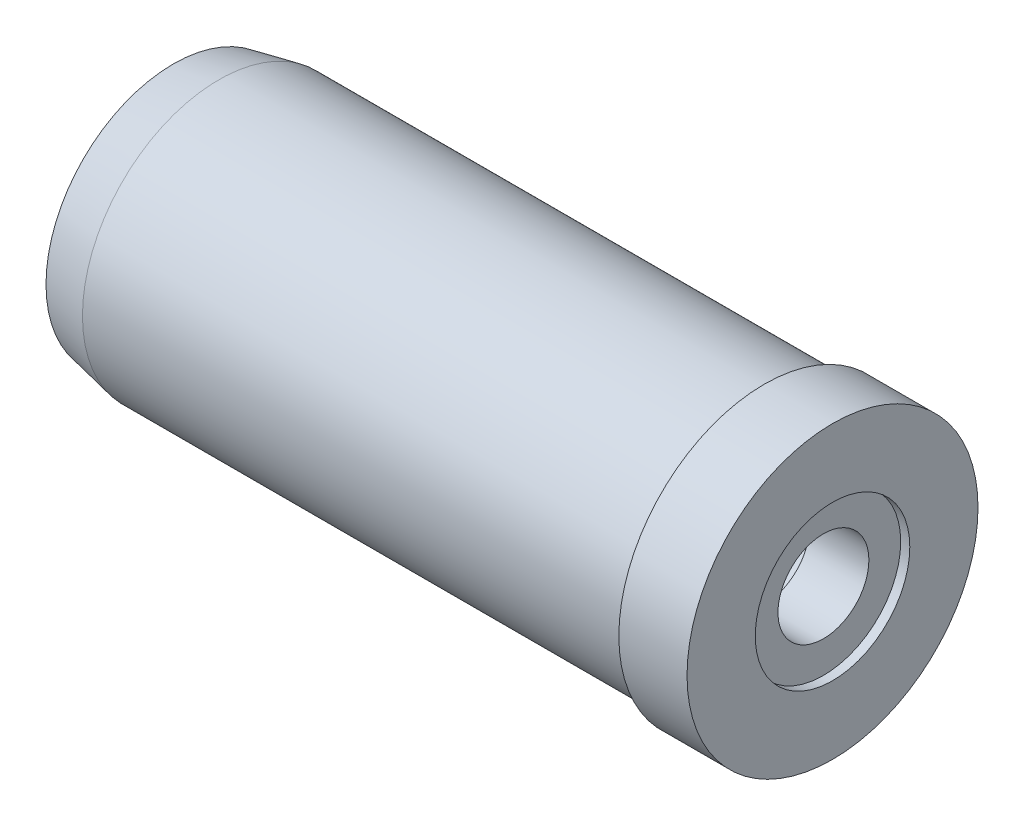
SolidWorks part; units mm, degrees
material "Alliage 1060"
ref_plane "Plan de face" through (0, 0, 0) normal (0, 0, 1) x (1, 0, 0)
ref_plane "Plan de dessus" through (0, 0, 0) normal (0, 1, 0) x (1, 0, 0)
ref_plane "Plan de droite" through (0, 0, 0) normal (1, 0, 0) x (0, 0, -1)
sketch "Esquisse1" plane through (0, 0, 0) normal (0, 0, 1) x (1, 0, 0)
  line L0 (175.5498, 10) -> (175.5498, 17)
  line L1 (175.5498, 17) -> (177.5498, 17)
  line L2 (177.5498, 17) -> (177.5498, 32)
  line L3 (177.5498, 32) -> (162.5498, 32)
  line L4 (162.5498, 32) -> (162.5498, 30)
  line L5 (162.5498, 30) -> (42.5664, 30)
  line L6 (42.5664, 30) -> (32.5498, 28)
  line L7 (32.5498, 28) -> (32.5498, 24)
  line L8 (32.5498, 24) -> (162.5498, 24)
  line L9 (162.5498, 24) -> (162.5498, 10)
  line L10 (162.5498, 10) -> (175.5498, 10)
  line L11 (32.5498, 0) -> (177.5498, 0) construction
revolve "Révolution1" add sketch "Esquisse1" angle 360 about L11
